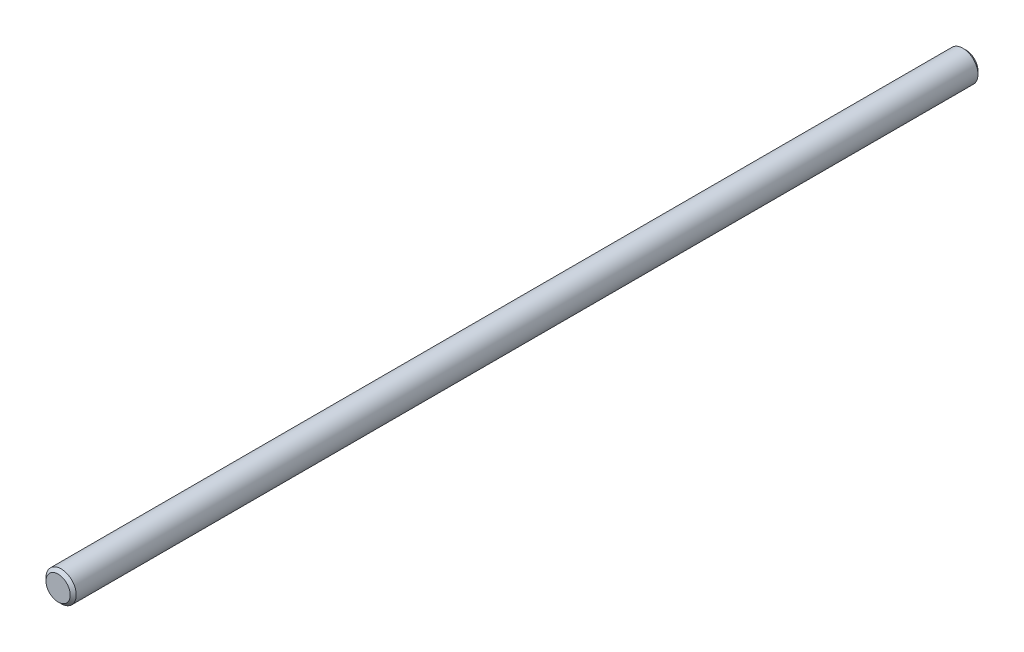
SolidWorks part; units mm, degrees
ref_plane "Front" through (0, 0, 0) normal (0, 0, 1) x (1, 0, 0)
ref_plane "Top" through (0, 0, 0) normal (0, 1, 0) x (1, 0, 0)
ref_plane "Right" through (0, 0, 0) normal (1, 0, 0) x (0, 0, -1)
sketch "Sketch1" plane through (0, 0, 0) normal (0, 0, 1) x (1, 0, 0)
  circle A0 centre (0, 0) radius 10
  dimension "D1" = 20
extrude "Extrude1" add sketch "Sketch1" along normal mid plane 600
chamfer "Chamfer1" distance 2 angle 45 2 edges at (10, 0, -300) (10, 0, 300)
equation "\"D1@Chamfer1\" = \"D1@Sketch1\" * .1"
